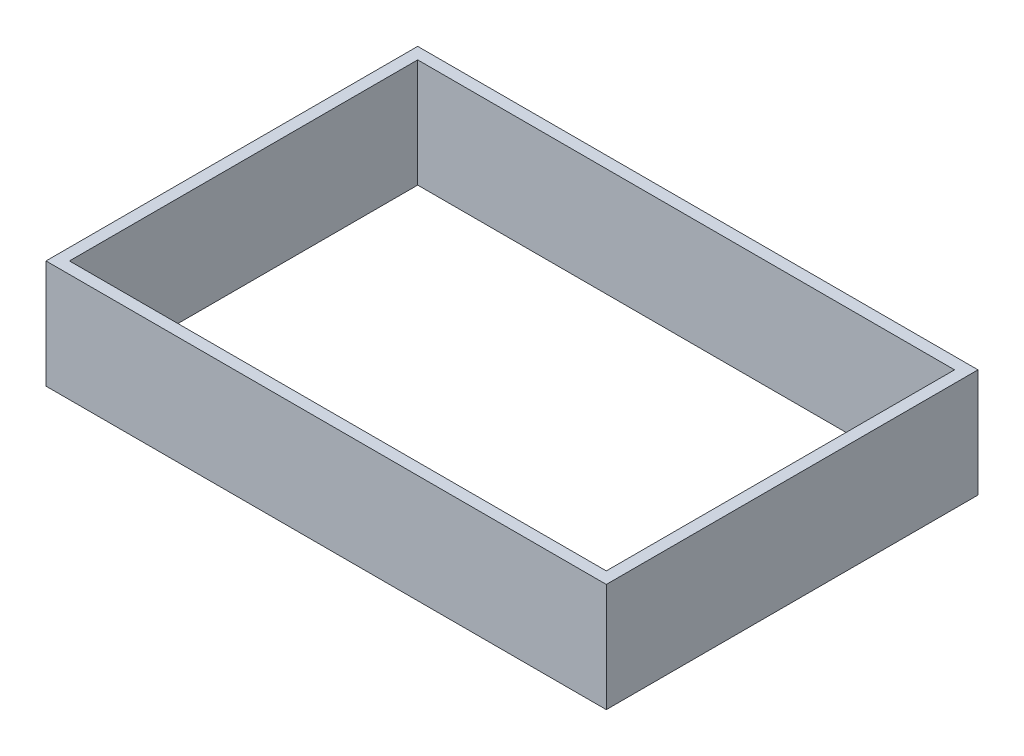
SolidWorks part; units mm, degrees
ref_plane "前视基准面" through (0, 0, 0) normal (0, 0, 1) x (1, 0, 0)
ref_plane "上视基准面" through (0, 0, 0) normal (0, 1, 0) x (1, 0, 0)
ref_plane "右视基准面" through (0, 0, 0) normal (1, 0, 0) x (0, 0, -1)
other "Configuration Table"
sketch "草图1" plane through (0, 0, 0) normal (0, 1, 0) x (1, 0, 0)
  line L0 (0, 47) -> (2, 47)
  line L1 (0, 0) -> (91.17, 0)
  line L2 (0, 0) -> (0, 59)
  line L3 (0, 59) -> (91.17, 59)
  line L4 (91.17, 0) -> (91.17, 59)
  line L5 (2, 57) -> (74.17, 57)
  line L6 (2, 57) -> (2, 2)
  line L7 (2, 2) -> (74.17, 2)
  line L8 (74.17, 57) -> (74.17, 2)
  line L9 (76.17, 57) -> (89.17, 57)
  line L10 (76.17, 57) -> (76.17, 2)
  line L11 (76.17, 2) -> (89.17, 2)
  line L12 (89.17, 57) -> (89.17, 2)
  line L13 (0, 34) -> (2, 34)
  line L14 (0, 15.7) -> (2, 15.7)
  line L15 (0, 5.3) -> (2, 5.3)
  dimension "D1" = 87.17
  dimension "D2" = 55
  dimension "D3" = 2
  dimension "D4" = 2
  dimension "D5" = 2
  dimension "D6" = 2
  dimension "D7" = 2
  dimension "D8" = 72.17
  dimension "D9" = 10
  dimension "D10" = 13
  dimension "D11" = 10.4
  dimension "D12" = 3.3
sketch "草图2" plane through (0, 0, 0) normal (0, 1, 0) x (1, 0, 0)
  line L1 (-0.2, 59.2) -> (91.37, 59.2)
  line L2 (-0.2, 59.2) -> (-0.2, -0.2)
  line L3 (-0.2, -0.2) -> (91.37, -0.2)
  line L4 (91.37, 59.2) -> (91.37, -0.2)
  line L5 (-2.2, 61.2) -> (93.37, 61.2)
  line L6 (-2.2, 61.2) -> (-2.2, -2.2)
  line L7 (-2.2, -2.2) -> (93.37, -2.2)
  line L8 (93.37, 61.2) -> (93.37, -2.2)
  line L10 (-0.2, 5.3) -> (-0.2, 4.5641)
  line L13 (76.17, 59.2) -> (74.17, 59.2)
  line L14 (76.17, 59.2) -> (76.17, -0.2)
  line L15 (76.17, -0.2) -> (74.17, -0.2)
  line L16 (74.17, 59.2) -> (74.17, -0.2)
  line L21 (-0.2, 59.2) -> (16.8, 59.2)
  line L22 (-0.2, 59.2) -> (-0.2, -0.2)
  line L23 (-0.2, -0.2) -> (16.8, -0.2)
  line L24 (16.8, 59.2) -> (16.8, -0.2)
  line L26 (16.8, 49.8092) -> (16.8, 10.173)
  line L32 (16.8, 28.3664) -> (16.8, 4.8641)
  line L34 (76.17, 59.2) -> (76.17, 17.0331)
  line L47 (76.17, -0.2) -> (76.17, -2.2)
  line L48 (0, 0) -> (0, 59) construction
  line L49 (-0.2, 47) -> (-2.2, 47)
  line L50 (0, 59) -> (91.17, 59) construction
  line L51 (91.17, 0) -> (91.17, 59) construction
  line L52 (76.17, 57) -> (76.17, 2) construction
  line L53 (74.17, 49.2) -> (64.17, 49.2)
  line L54 (16.8, 44.2) -> (64.17, 44.2)
  line L55 (16.8, 44.2) -> (16.8, 13)
  line L56 (16.8, 13) -> (64.17, 13)
  line L57 (64.17, 44.2) -> (64.17, 13)
  line L58 (74.17, 49.2) -> (74.17, 8)
  line L59 (74.17, 8) -> (64.17, 8)
  line L60 (64.17, 49.2) -> (64.17, 8)
  line L61 (-0.2, 34) -> (-2.2, 34)
  line L62 (-0.2, 15.7) -> (-2.2, 15.7)
  line L63 (-0.2, 5.3) -> (-2.2, 5.3)
  line L64 (0, 5.3) -> (2, 5.3) construction
  line L65 (0, 15.7) -> (2, 15.7) construction
  line L66 (0, 34) -> (2, 34) construction
  line L67 (0, 47) -> (2, 47) construction
  line L69 (-0.2, 47) -> (13.8, 47)
  line L70 (-0.2, 47) -> (-0.2, 34)
  line L71 (-0.2, 34) -> (13.8, 34)
  line L72 (13.8, 47) -> (13.8, 34)
  line L73 (-0.2, 15.7) -> (13.8, 15.7)
  line L74 (-0.2, 15.7) -> (-0.2, 5.3)
  line L75 (-0.2, 5.3) -> (13.8, 5.3)
  line L76 (13.8, 15.7) -> (13.8, 5.3)
  line L77 (-0.2, 50.2) -> (13.8, 50.2)
  line L78 (-0.2, 50.2) -> (-0.2, 59.2)
  line L79 (-0.2, 59.2) -> (13.8, 59.2)
  line L80 (13.8, 50.2) -> (13.8, 59.2)
  line L81 (20.8, 38.5) -> (34.1026, 38.5)
  line L82 (20.8, 38.5) -> (20.8, 18.5)
  line L83 (20.8, 18.5) -> (34.1026, 18.5)
  line L84 (34.1026, 38.5) -> (34.1026, 18.5)
  line L85 (38.67, 38.5) -> (58.67, 38.5)
  line L86 (38.67, 38.5) -> (38.67, 18.5)
  line L87 (38.67, 18.5) -> (58.67, 18.5)
  line L88 (58.67, 38.5) -> (58.67, 18.5)
  line L89 (74.17, 38.5) -> (65.17, 38.5)
  line L90 (74.17, 38.5) -> (74.17, 18.5)
  line L91 (74.17, 18.5) -> (65.17, 18.5)
  line L92 (65.17, 38.5) -> (65.17, 18.5)
  dimension "D1" = 0.2
  dimension "D2" = 0.2
  dimension "D3" = 0.2
  dimension "D4" = 0.2
  dimension "D5" = 2
  dimension "D6" = 2
  dimension "D7" = 2
  dimension "D8" = 2
  dimension "D9" = 2
  dimension "D10" = 17
  dimension "D11" = 10
  dimension "D12" = 10
  dimension "D13" = 8.2
  dimension "D14" = 5
  dimension "D15" = 5
  dimension "D16" = 9
  dimension "D17" = 13
  dimension "D18" = 14
  dimension "D19" = 5.5
  dimension "D20" = 20
  dimension "D21" = 5.5
  dimension "D22" = 5.5
  dimension "D23" = 13.3026
  dimension "D24" = 4
  dimension "D25" = 9
extrude "凸台-拉伸1" add sketch "草图2" against normal blind 18.5 contours L2 L63 L6 L7 L47 L3 | L63 L22 L62 L6 | L62 L2 L61 L6 | L61 L22 L49 L6 | L49 L22 L2 L1 L21 L4 L3 L47 L7 L8 L5 L6
